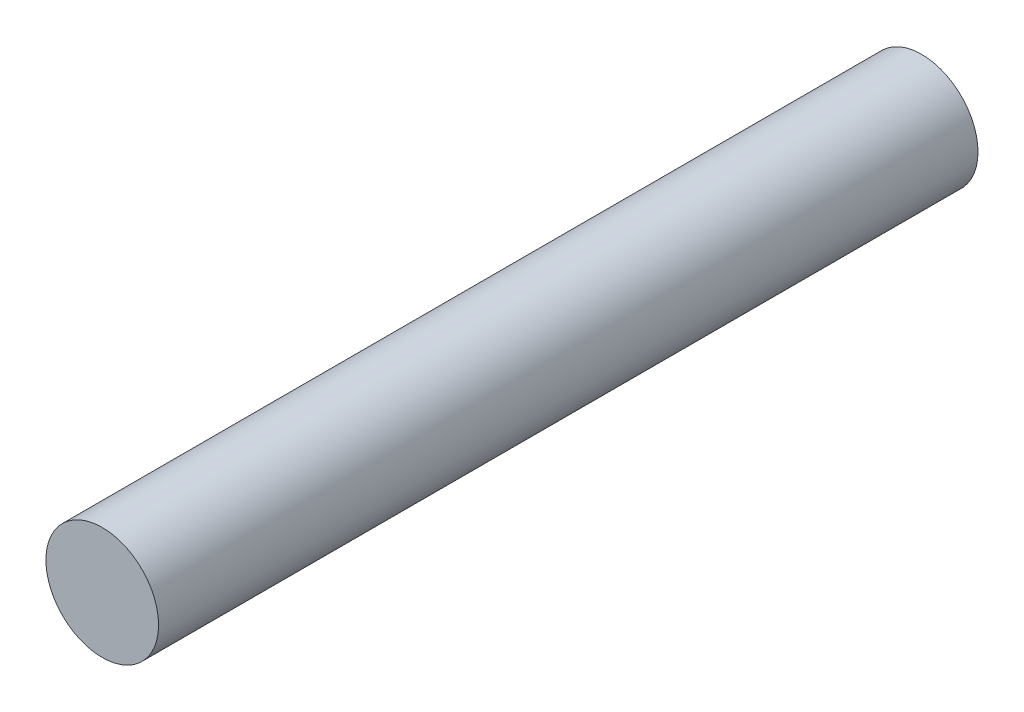
SolidWorks part; units mm, degrees
ref_plane "Ön Düzlem" through (0, 0, 0) normal (0, 0, 1) x (1, 0, 0)
ref_plane "Üst Düzlem" through (0, 0, 0) normal (0, 1, 0) x (1, 0, 0)
ref_plane "Sağ Düzlem" through (0, 0, 0) normal (1, 0, 0) x (0, 0, -1)
sketch "Çizim1" plane through (0, 0, 0) normal (0, 0, 1) x (1, 0, 0)
  circle A0 centre (0, 0) radius 2.75
  dimension "D1" = 5.5
extrude "Yükseklik-Ekstrüzyon1" add sketch "Çizim1" along normal blind 40
